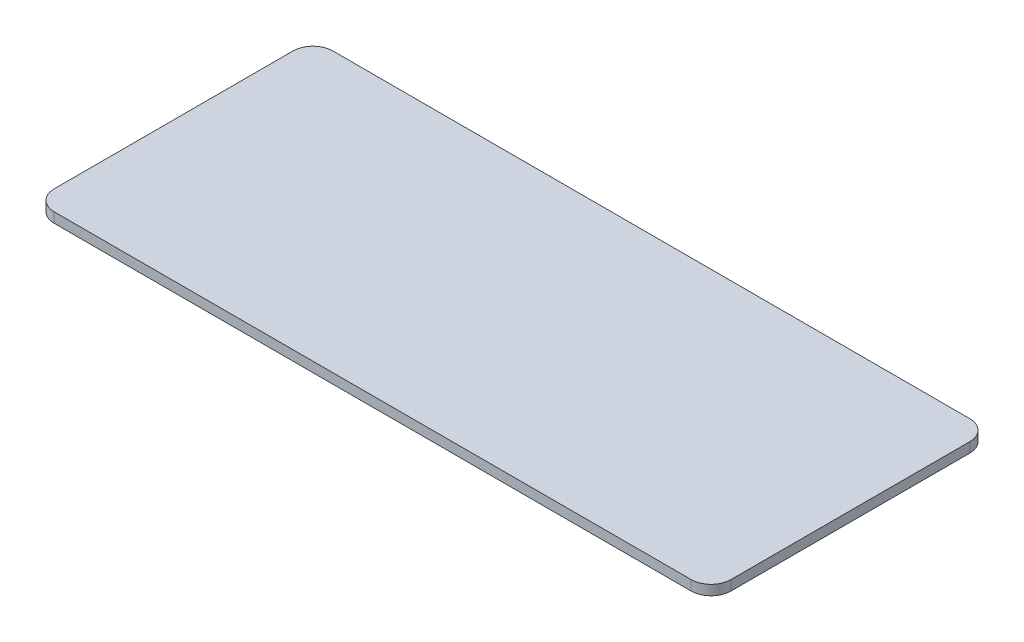
SolidWorks part; units mm, degrees
ref_plane "前视基准面" through (0, 0, 0) normal (0, 0, 1) x (1, 0, 0)
ref_plane "上视基准面" through (0, 0, 0) normal (0, 1, 0) x (1, 0, 0)
ref_plane "右视基准面" through (0, 0, 0) normal (1, 0, 0) x (0, 0, -1)
sketch "草图1" plane through (0, 0, 0) normal (0, 1, 0) x (1, 0, 0)
  line L1 (-33.3668, 14.7789) -> (30.6332, 14.7789)
  line L2 (-35.3668, 12.7789) -> (-35.3668, -11.2211)
  line L3 (-33.3668, -13.2211) -> (30.6332, -13.2211)
  line L4 (32.6332, 12.7789) -> (32.6332, -11.2211)
  arc A0 (30.6332, 14.7789) -> (32.6332, 12.7789) centre (30.6332, 12.7789) cw
  arc A1 (30.6332, -13.2211) -> (32.6332, -11.2211) centre (30.6332, -11.2211) ccw
  arc A2 (-35.3668, -11.2211) -> (-33.3668, -13.2211) centre (-33.3668, -11.2211) ccw
  arc A3 (-33.3668, 14.7789) -> (-35.3668, 12.7789) centre (-33.3668, 12.7789) ccw
  point P6 (32.6332, 14.7789)
  point P9 (32.6332, -13.2211)
  point P14 (-35.3668, 14.7789)
  dimension "D3" = 2
  dimension "D1" = 68
  dimension "D2" = 28
extrude "凸台-拉伸1" add sketch "草图1" along normal blind 1
